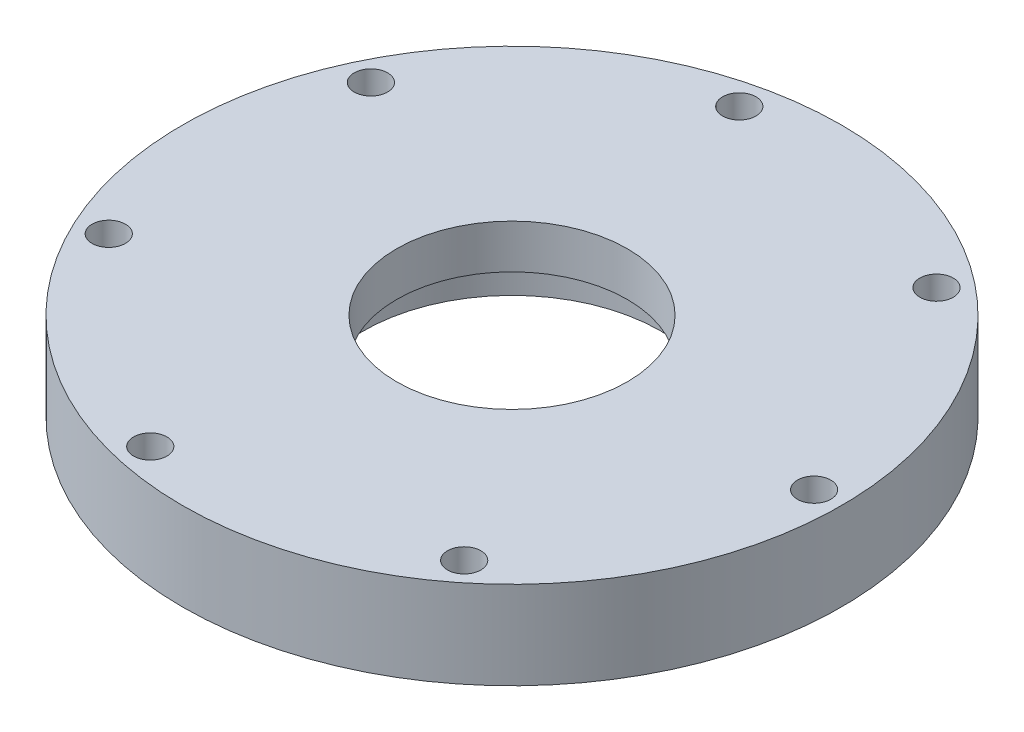
SolidWorks part; units mm, degrees
ref_plane "Alzado" through (0, 0, 0) normal (0, 0, 1) x (1, 0, 0)
ref_plane "Planta" through (0, 0, 0) normal (0, 1, 0) x (1, 0, 0)
ref_plane "Vista lateral" through (0, 0, 0) normal (1, 0, 0) x (0, 0, -1)
sketch "Croquis1" plane through (0, 0, 0) normal (0, 1, 0) x (1, 0, 0)
  circle A0 centre (0, 0) radius 30
  circle A1 centre (0, 0) radius 10.5
  dimension "D1" = 60
  dimension "D2" = 21
extrude "Saliente-Extruir1" add sketch "Croquis1" along normal blind 8
sketch "Croquis2" plane through (0, 0, 0) normal (0, -1, 0) x (1, 0, 0)
  circle A0 centre (0, 0) radius 13.53
  dimension "D1" = 27.06
extrude "Cortar-Extruir1" cut sketch "Croquis2" against normal blind 4
sketch "Croquis3" plane through (0, 8, 0) normal (0, 1, 0) x (1, 0, 0)
  circle A0 centre (27.5, 0) radius 1.52
  circle A1 centre (17.146, -21.5004) radius 1.52
  circle A2 centre (-6.1193, -26.8105) radius 1.52
  circle A3 centre (-24.7766, -11.9318) radius 1.52
  circle A4 centre (-24.7766, 11.9318) radius 1.52
  circle A5 centre (-6.1193, 26.8105) radius 1.52
  circle A6 centre (17.146, 21.5004) radius 1.52
  point P18 (0, 0)
  dimension "D2" = 3.04
  dimension "D1" = 27.5
  dimension "D3" = 7
extrude "Cortar-Extruir2" cut sketch "Croquis3" against normal through all
